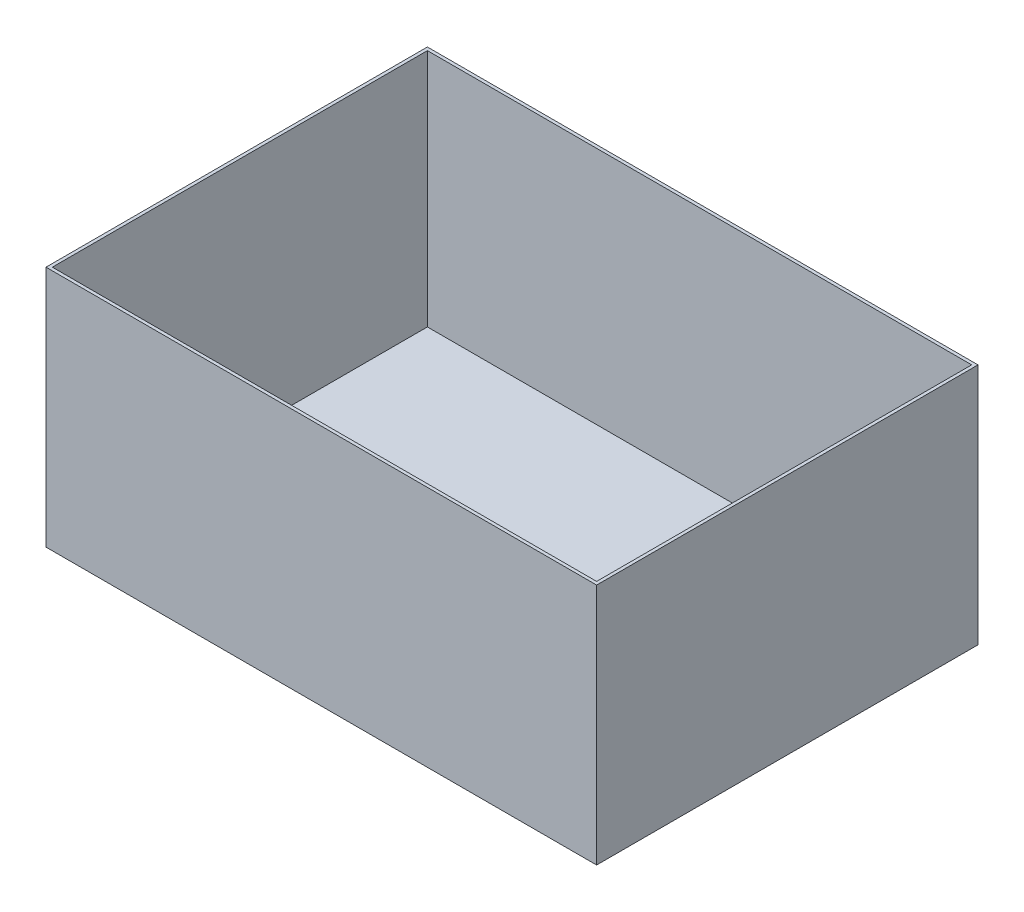
SolidWorks part; units mm, degrees
ref_plane "Front Plane" through (0, 0, 0) normal (0, 0, 1) x (1, 0, 0)
ref_plane "Top Plane" through (0, 0, 0) normal (0, 1, 0) x (1, 0, 0)
ref_plane "Right Plane" through (0, 0, 0) normal (1, 0, 0) x (0, 0, -1)
sketch "Sketch1" plane through (0, 0, 0) normal (0, 1, 0) x (1, 0, 0)
  line L1 (-276.86, 191.77) -> (276.86, 191.77)
  line L2 (-276.86, 191.77) -> (-276.86, -191.77)
  line L3 (-276.86, -191.77) -> (276.86, -191.77)
  line L4 (276.86, 191.77) -> (276.86, -191.77)
  line L5 (-276.86, 191.77) -> (276.86, -191.77) construction
  line L6 (-276.86, -191.77) -> (276.86, 191.77) construction
  point P0 (0, 0)
  dimension "D1" = 553.72
  dimension "D2" = 383.54
extrude "Boss-Extrude1" add sketch "Sketch1" along normal blind 243.84
shell "Shell1" thickness 3.175
